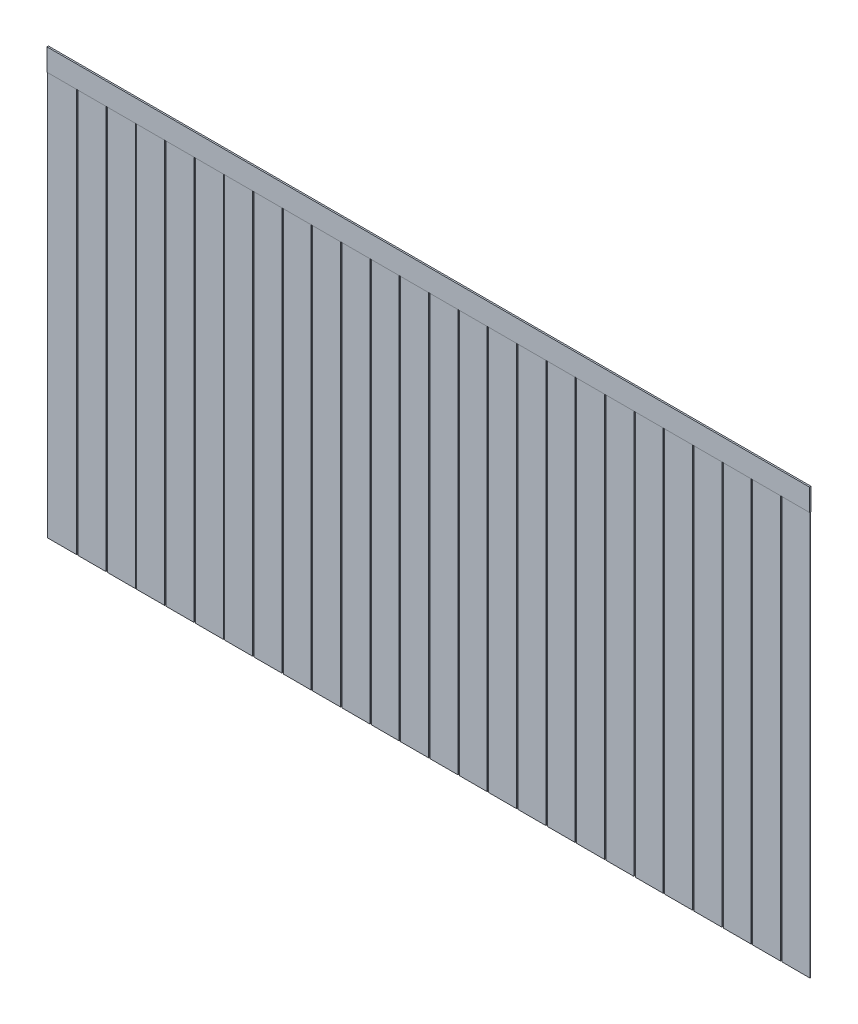
SolidWorks part; units mm, degrees
ref_plane "Alzado" through (0, 0, 0) normal (0, 0, 1) x (1, 0, 0)
ref_plane "Planta" through (0, 0, 0) normal (0, 1, 0) x (1, 0, 0)
ref_plane "Vista lateral" through (0, 0, 0) normal (1, 0, 0) x (0, 0, -1)
sketch "Croquis1" plane through (0, 0, 0) normal (0, 0, 1) x (1, 0, 0)
  line L1 (0, 0) -> (5200, 0)
  line L2 (0, 0) -> (0, -2900)
  line L3 (0, -2900) -> (5200, -2900)
  line L4 (5200, 0) -> (5200, -2900)
  dimension "D1" = 5200
  dimension "D2" = 2900
extrude "Saliente-Extruir1" add sketch "Croquis1" along normal blind 10
sketch "Croquis2" plane through (0, 0, 10) normal (0, 0, 1) x (1, 0, 0)
  line L0 (0, -2900) -> (5200, -2900) construction
  line L1 (200, -2900) -> (210, -2900)
  line L2 (200, -2900) -> (200, -150)
  line L3 (200, -150) -> (210, -150)
  line L4 (210, -2900) -> (210, -150)
  line L5 (0, 0) -> (0, -2900) construction
  line L6 (5200, 0) -> (0, 0) construction
  dimension "D1" = 200
  dimension "D2" = 150
  dimension "D3" = 10
extrude "Cortar-Extruir1" cut sketch "Croquis2" against normal blind 10
pattern_linear "MatrizL1" count 25 spacing 200 along (1, 0, 0) of "Cortar-Extruir1"
sketch "Croquis4" plane through (0, 0, 10) normal (0, 0, 1) x (1, 0, 0)
  line L0 (5200, -2900) -> (5200, 0) construction
  line L1 (0, -2900) -> (5200, -2900)
  line L2 (0, -2900) -> (0, -150)
  line L3 (0, -150) -> (5200, -150)
  line L4 (5200, -2900) -> (5200, -150)
extrude "Cortar-Extruir2" cut sketch "Croquis4" against normal blind 2
sketch "Croquis5" plane through (0, 0, 0) normal (0, 0, -1) x (-1, 0, 0)
  line L0 (0, 0) -> (0, -2900) construction
  line L1 (-5200, -2900) -> (0, -2900)
  line L2 (-5200, -2900) -> (-5200, -150)
  line L3 (-5200, -150) -> (0, -150)
  line L4 (0, -2900) -> (0, -150)
extrude "Cortar-Extruir3" cut sketch "Croquis5" against normal blind 2
